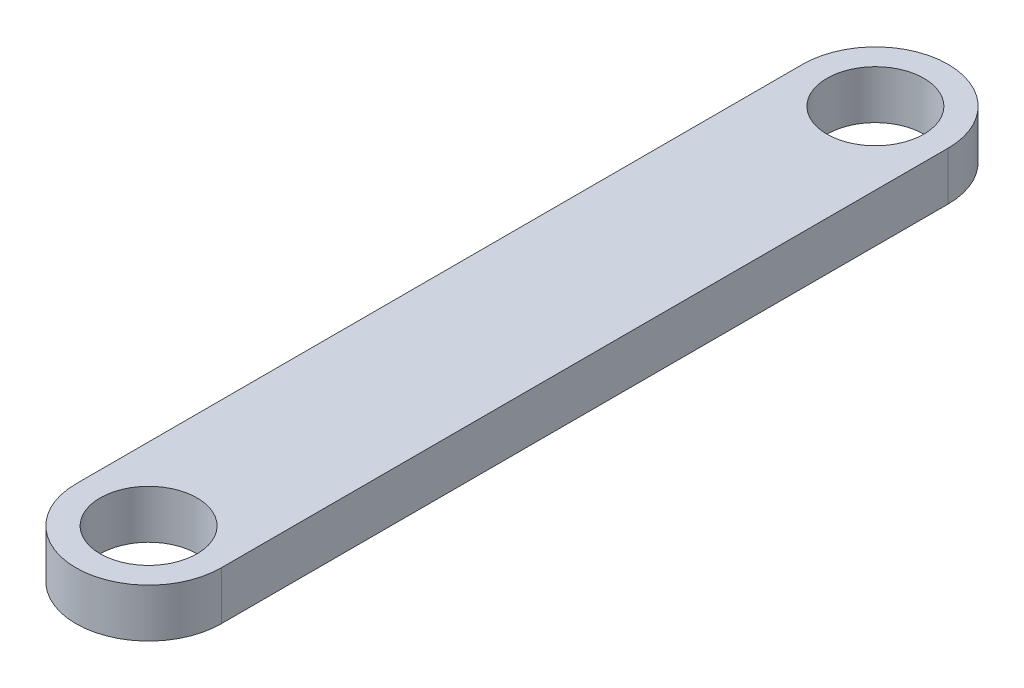
SolidWorks part; units mm, degrees
ref_plane "Front Plane" through (0, 0, 0) normal (0, 0, 1) x (1, 0, 0)
ref_plane "Top Plane" through (0, 0, 0) normal (0, 1, 0) x (1, 0, 0)
ref_plane "Right Plane" through (0, 0, 0) normal (1, 0, 0) x (0, 0, -1)
sketch "Sketch1" plane through (0, 0, 0) normal (0, 1, 0) x (1, 0, 0)
  line L0 (0, -24.4177) -> (0, 51.788) construction
  line L1 (-3, 0) -> (-3, 30)
  line L3 (3, 30) -> (3, 0)
  arc A0 (-3, 30) -> (3, 30) centre (0, 30) cw
  arc A1 (-3, 0) -> (3, 0) centre (0, 0) ccw
  circle A2 centre (0, 30) radius 2
  circle A3 centre (0, 0) radius 2
  dimension "D3" = 4
  dimension "D4" = 4
  dimension "D1" = 6
  dimension "D2" = 30
extrude "Boss-Extrude1" add sketch "Sketch1" along normal blind 2
